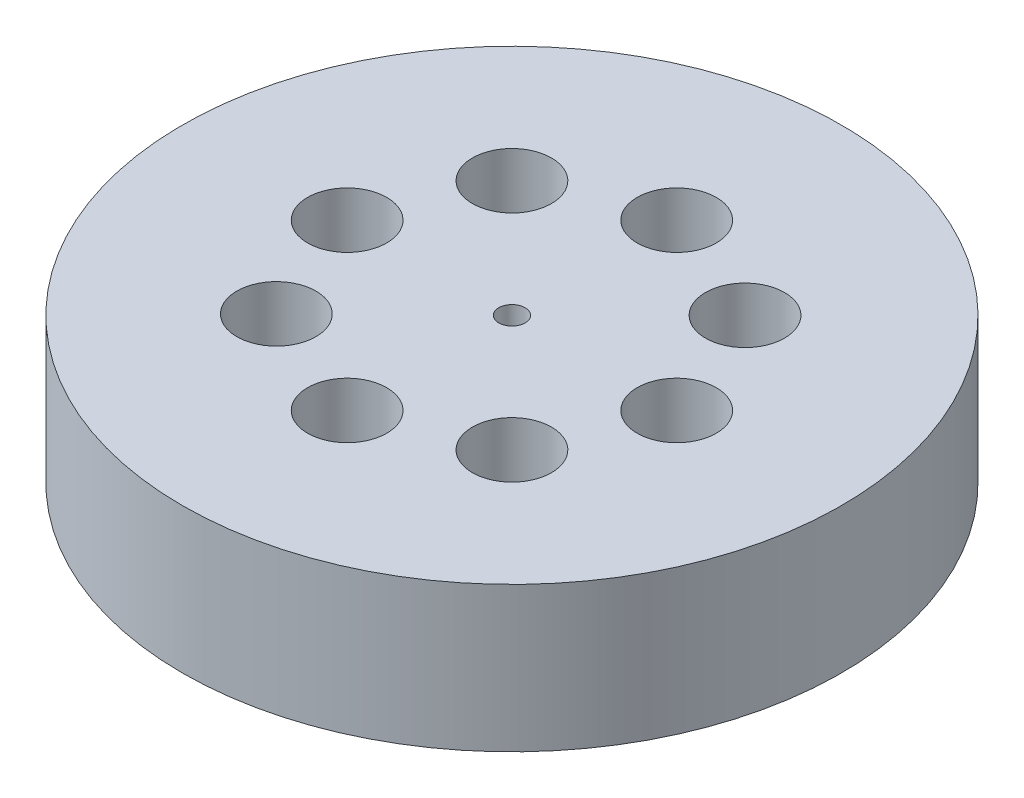
SolidWorks part; units mm, degrees
ref_plane "Plan de face" through (0, 0, 0) normal (0, 0, 1) x (1, 0, 0)
ref_plane "Plan de dessus" through (0, 0, 0) normal (0, 1, 0) x (1, 0, 0)
ref_plane "Plan de droite" through (0, 0, 0) normal (1, 0, 0) x (0, 0, -1)
sketch "Esquisse1" plane through (0, 0, 0) normal (0, 1, 0) x (1, 0, 0)
  circle A0 centre (0, 0) radius 50
extrude "Boss.-Extru.1" add sketch "Esquisse1" along normal blind 22
sketch "Esquisse5" plane through (0, 0, 0) normal (0, -1, 0) x (-1, 0, 0)
  circle A0 centre (25, 0) radius 6
  circle A1 centre (0, 25) radius 6
  circle A2 centre (-17.68, 17.68) radius 6
  circle A3 centre (17.68, -17.68) radius 6
  circle A4 centre (0, -25) radius 6
  circle A5 centre (-17.68, -17.68) radius 6
  circle A6 centre (17.68, 17.68) radius 6
  circle A7 centre (-25, 0) radius 6
extrude "Enlèv. mat.-Extru.6" cut sketch "Esquisse5" against normal blind 22 contours A2
sketch "Esquisse7" plane through (0, 0, 0) normal (0, -1, 0) x (-1, 0, 0)
  circle A0 centre (18.0581, -17.68) radius 6
extrude "Enlèv. mat.-Extru.7" cut sketch "Esquisse7" against normal blind 22
sketch "Esquisse8" plane through (0, 0, 0) normal (0, -1, 0) x (-1, 0, 0)
  circle A0 centre (17.68, 17.68) radius 6
extrude "Enlèv. mat.-Extru.8" cut sketch "Esquisse8" against normal blind 22
sketch "Esquisse9" plane through (0, 0, 0) normal (0, -1, 0) x (-1, 0, 0)
  circle A0 centre (-17.68, -17.68) radius 6
extrude "Enlèv. mat.-Extru.9" cut sketch "Esquisse9" against normal blind 22
sketch "Esquisse10" plane through (0, 0, 0) normal (0, -1, 0) x (1, 0, 0)
  circle A0 centre (0, 25) radius 6
extrude "Enlèv. mat.-Extru.10" cut sketch "Esquisse10" against normal blind 22
sketch "Esquisse11" plane through (0, 0, 0) normal (0, -1, 0) x (-1, 0, 0)
  circle A0 centre (25, 0) radius 6
extrude "Enlèv. mat.-Extru.11" cut sketch "Esquisse11" against normal blind 22
sketch "Esquisse12" plane through (0, 0, 0) normal (0, -1, 0) x (-1, 0, 0)
  circle A0 centre (-25, 0) radius 6
extrude "Enlèv. mat.-Extru.12" cut sketch "Esquisse12" against normal blind 22
sketch "Esquisse13" plane through (0, 0, 0) normal (0, -1, 0) x (-1, 0, 0)
  circle A0 centre (0, 25) radius 6
extrude "Enlèv. mat.-Extru.13" cut sketch "Esquisse13" against normal blind 22
sketch "Esquisse14" plane through (0, 0, 0) normal (0, -1, 0) x (-1, 0, 0)
  circle A0 centre (0, 0) radius 10
extrude "Enlèv. mat.-Extru.15" cut sketch "Esquisse14" against normal blind 18
sketch "Esquisse15" plane through (0, 18, 0) normal (0, -1, 0) x (-1, 0, 0)
  circle A0 centre (0, 0) radius 2
extrude "Enlèv. mat.-Extru.16" cut sketch "Esquisse15" against normal blind 4
